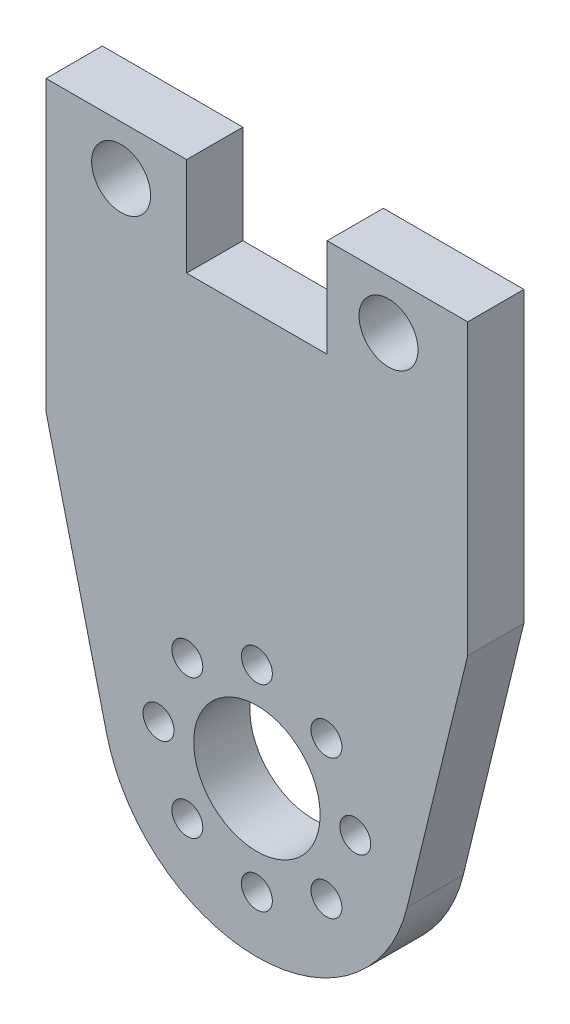
SolidWorks part; units mm, degrees
ref_plane "Plan de face" through (0, 0, 0) normal (0, 0, 1) x (1, 0, 0)
ref_plane "Plan de dessus" through (0, 0, 0) normal (0, 1, 0) x (1, 0, 0)
ref_plane "Plan de droite" through (0, 0, 0) normal (1, 0, 0) x (0, 0, -1)
sketch "Esquisse1" plane through (0, 0, 0) normal (0, 0, 1) x (1, 0, 0)
  line L0 (-15, 3) -> (-15, 7)
  line L1 (-15, 7) -> (-5, 7)
  line L2 (-5, 7) -> (-5, 0)
  line L3 (-5, 0) -> (5, 0)
  line L4 (5, 0) -> (5, 7)
  line L5 (5, 7) -> (15, 7)
  line L6 (15, 7) -> (15, 3)
  line L7 (-15, 3) -> (-15, -13.5741)
  line L8 (15, 3) -> (15, -13.5741)
  line L9 (0, 9.0284) -> (0, -50.6802) construction
  line L16 (-15, -13.5741) -> (-10.6864, -31.2508)
  line L18 (0, -28.643) -> (-11, -28.643) construction
  line L22 (15, -13.5741) -> (10.6864, -31.2508)
  circle A20 centre (0, -28.643) radius 4.5
  circle A21 centre (0, -21.643) radius 1.1
  circle A22 centre (0, -28.643) radius 4.5
  circle A23 centre (4.9497, -23.6933) radius 1.1
  circle A24 centre (0, -28.643) radius 4.5
  circle A25 centre (7, -28.643) radius 1.1
  circle A26 centre (0, -28.643) radius 4.5
  circle A27 centre (4.9497, -33.5928) radius 1.1
  circle A28 centre (0, -28.643) radius 4.5
  circle A29 centre (0, -35.643) radius 1.1
  circle A30 centre (0, -28.643) radius 4.5
  circle A31 centre (-4.9497, -33.5928) radius 1.1
  circle A32 centre (0, -28.643) radius 4.5
  circle A33 centre (-7, -28.643) radius 1.1
  circle A34 centre (0, -28.643) radius 4.5
  circle A35 centre (-4.9497, -23.6933) radius 1.1
  arc A39 (-10.6864, -31.2508) -> (10.6864, -31.2508) centre (0, -28.643) ccw
  point P2 (0, 0)
  dimension "D7" = 11
  dimension "D12" = 9
  dimension "D13" = 2.2
  dimension "D1" = 30
  dimension "D2" = 4
  dimension "D3" = 4
  dimension "D4" = 10
  dimension "D5" = 7
  dimension "D6" = 7
  dimension "D10" = 8
  dimension "D14" = 7
extrude "Boss.-Extru.1" add sketch "Esquisse1" along normal blind 4
sketch "Sketch1" plane through (0, 0, 0) normal (0, 0, -1) x (-1, 0, 0)
  circle A0 centre (-9.368, 3.5) radius 2.1
  circle A1 centre (9.6636, 3.5) radius 2.1
extrude "Cut-Extrude1" cut sketch "Sketch1" against normal through all
